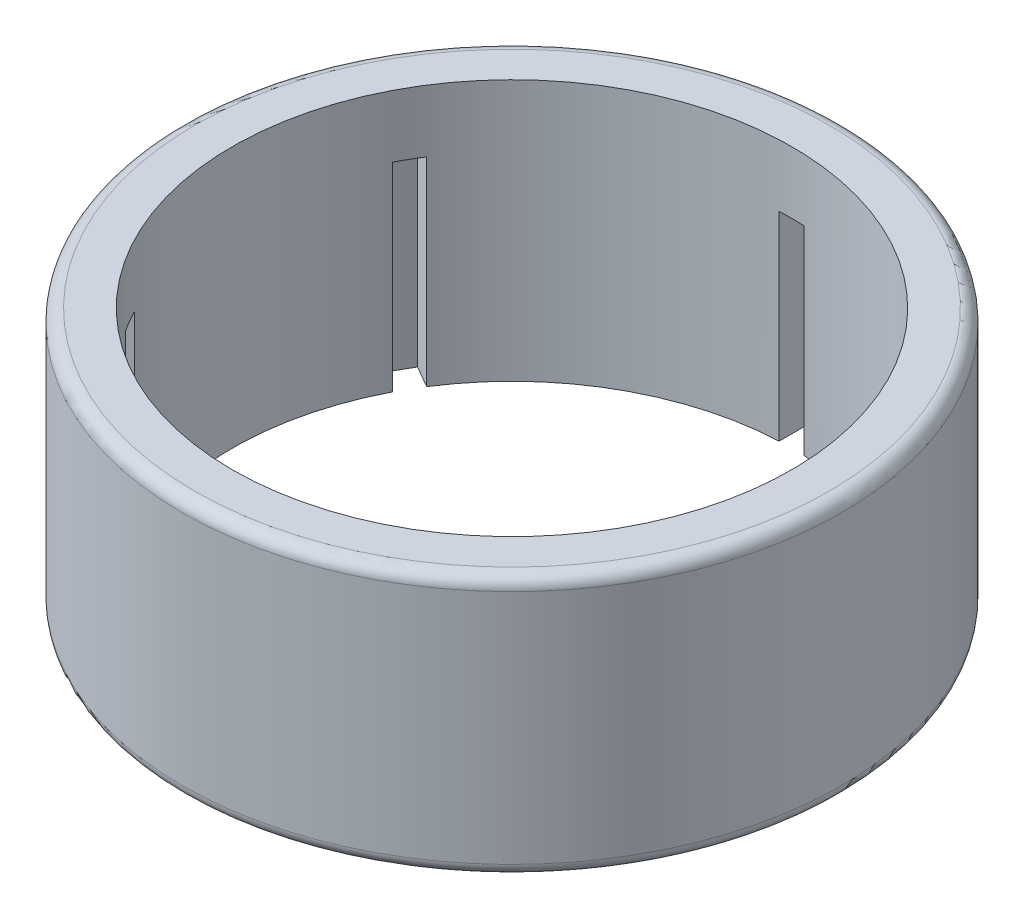
SolidWorks part; units mm, degrees
material "聚亚安酯(11671)"
ref_plane "前视基准面" through (0, 0, 0) normal (0, 0, 1) x (1, 0, 0)
ref_plane "上视基准面" through (0, 0, 0) normal (0, 1, 0) x (1, 0, 0)
ref_plane "右视基准面" through (0, 0, 0) normal (1, 0, 0) x (0, 0, -1)
other "Configuration Table"
sketch "草图1" plane through (0, 0, 0) normal (0, 1, 0) x (1, 0, 0)
  circle A0 centre (0, 0) radius 22.5
  circle A1 centre (0, 0) radius 26.5
  dimension "D1" = 45
  dimension "D2" = 53
extrude "凸台-拉伸1" add sketch "草图1" along normal blind 21
sketch "草图2" plane through (0, 0, 0) normal (0, -1, 0) x (1, 0, 0)
  line L0 (0, -35.5928) -> (0, 35.5928) construction
  line L1 (-1, 22.4778) -> (-1, 24.4778)
  line L2 (-1, 24.4778) -> (1, 24.4778)
  line L3 (1, 24.4778) -> (1, 22.4778)
  circle A0 centre (0, 0) radius 22.5 construction
  circle A1 centre (0, 0) radius 22.5
  point P4 (0, 0)
  circle M2 centre (0, 0) radius 22.5
  dimension "D1" = 2
  dimension "D2" = 2
extrude "切除-拉伸1" cut sketch "草图2" against normal offset from surface (16 mm away) 5 contours L0 L2 L1 M2 | L0 A1 L3 L2 up to face at (0, 21, 26.5)
pattern_circular "阵列(圆周)1" count 6 over 360 about axis through (0, 0, 0) along (0, 1, 0) of "切除-拉伸1"
fillet "圆角1" radius 1 2 edges at (0, 0, 26.5) (0, 21, 26.5)
